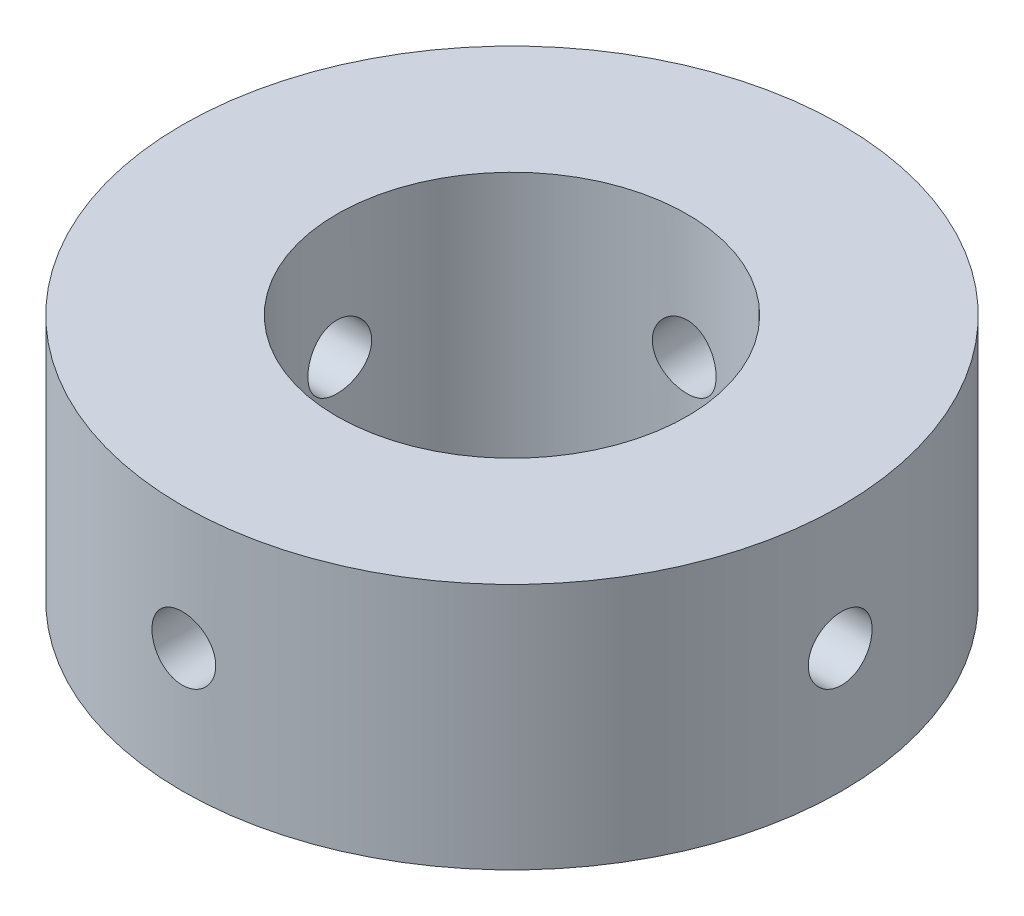
SolidWorks part; units mm, degrees
material "ABS"
ref_plane "Front Plane" through (0, 0, 0) normal (0, 0, 1) x (1, 0, 0)
ref_plane "Top Plane" through (0, 0, 0) normal (0, 1, 0) x (1, 0, 0)
ref_plane "Right Plane" through (0, 0, 0) normal (1, 0, 0) x (0, 0, -1)
sketch "Sketch1" plane through (0, 0, 0) normal (0, 1, 0) x (1, 0, 0)
  line L0 (0, 0) -> (25.4, 0) construction
  circle A0 centre (0, 0) radius 13.4938
  circle A1 centre (0, 0) radius 27.6225 construction
  circle A2 centre (0, 0) radius 25.4
  dimension "D1" = 26.9875
  dimension "D2" = 55.245
  dimension "D3" = 2.2225
extrude "Boss-Extrude1" add sketch "Sketch1" along normal blind 19.05
ref_plane "Plane1" through (25.4, 0, 0) normal (1, 0, 0) x (0, 0, -1)
sketch "Sketch2" plane through (25.4, 0, 0) normal (1, 0, 0) x (0, 0, -1)
  line L0 (0, 0) -> (0, 19.05) construction
  line L1 (13.4937, 19.05) -> (-13.4937, 19.05) construction
  point P5 (0, 9.525)
hole_wizard "#10 (0.1935) Diameter Hole1" positions "Sketch2" profile "Sketch3" hole size "#10" standard "ANSI Inch"
sketch "Sketch3" plane through (25.4, 9.525, 0) normal (0, 1, 0) x (0, 0, -1)
  line L0 (0, 0) -> (0, 11.9062)
  line L1 (0, 11.9062) -> (2.4574, 11.9062)
  line L2 (2.4574, 11.9062) -> (2.4574, 0)
  line L5 (2.4574, 0) -> (0, 0)
  line L11 (0, -6.35) -> (0, 107.95) construction
  dimension "Thru Hole Dia." = 4.9149
  dimension "Thru Hole Depth" = 11.9062
pattern_circular "CirPattern1" count 4 over 360 about axis through (0, 19.05, 0) along (0, -1, 0) of "#10 (0.1935) Diameter Hole1"
